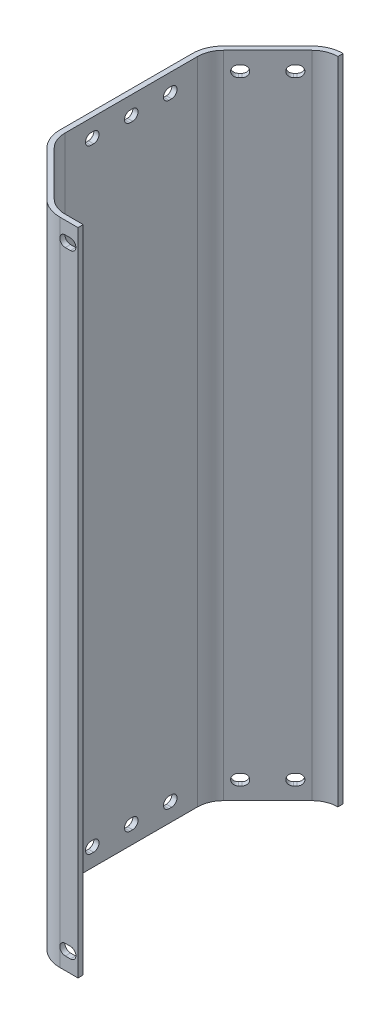
SolidWorks part; units mm, degrees
ref_plane "前视基准面" through (0, 0, 0) normal (0, 0, 1) x (1, 0, 0)
ref_plane "上视基准面" through (0, 0, 0) normal (0, 1, 0) x (1, 0, 0)
ref_plane "右视基准面" through (0, 0, 0) normal (1, 0, 0) x (0, 0, -1)
other "Configuration Table"
sketch "草图1" plane through (0, 0, 0) normal (0, 1, 0) x (1, 0, 0)
  line L0 (83.2331, 52.8648) -> (-81.774, 52.8648)
  line L1 (-88.8451, 49.9358) -> (-105.8415, 32.9394)
  line L2 (-108.7705, 25.8683) -> (-108.7705, -25.1388)
  line L3 (-105.8415, -32.2099) -> (-88.8451, -49.2063)
  line L4 (-81.774, -52.1352) -> (83.2331, -52.1352)
  line L5 (90.3042, -49.2063) -> (107.3006, -32.2099)
  line L6 (110.2295, -25.1388) -> (110.2295, 25.8683)
  line L7 (107.3006, 32.9394) -> (90.3042, 49.9358)
  arc A0 (-81.774, 52.8648) -> (-88.8451, 49.9358) centre (-81.774, 42.8648) ccw
  arc A1 (-105.8415, 32.9394) -> (-108.7705, 25.8683) centre (-98.7705, 25.8683) ccw
  arc A2 (-108.7705, -25.1388) -> (-105.8415, -32.2099) centre (-98.7705, -25.1388) ccw
  arc A3 (-88.8451, -49.2063) -> (-81.774, -52.1352) centre (-81.774, -42.1352) ccw
  arc A4 (83.2331, -52.1352) -> (90.3042, -49.2063) centre (83.2331, -42.1352) ccw
  arc A5 (107.3006, -32.2099) -> (110.2295, -25.1388) centre (100.2295, -25.1388) ccw
  arc A6 (110.2295, 25.8683) -> (107.3006, 32.9394) centre (100.2295, 25.8683) ccw
  arc A7 (90.3042, 49.9358) -> (83.2331, 52.8648) centre (83.2331, 42.8648) ccw
sketch "草图2" plane through (0, 0, 0) normal (0, 1, 0) x (1, 0, 0)
  line L0 (83.2331, 54.8648) -> (-81.774, 54.8648)
  line L1 (-90.2593, 51.35) -> (-107.2558, 34.3536)
  line L2 (-110.7705, 25.8683) -> (-110.7705, -25.1388)
  line L3 (-107.2558, -33.6241) -> (-90.2593, -50.6205)
  line L4 (-81.774, -54.1352) -> (83.2331, -54.1352)
  line L5 (91.7184, -50.6205) -> (108.7148, -33.6241)
  line L6 (112.2295, -25.1388) -> (112.2295, 25.8683)
  line L7 (108.7148, 34.3536) -> (91.7184, 51.35)
  line L8 (-81.774, -52.1352) -> (83.2331, -52.1352)
  line L9 (-105.8415, -32.2099) -> (-88.8451, -49.2063)
  line L10 (-108.7705, 25.8683) -> (-108.7705, -25.1388)
  line L11 (-88.8451, 49.9358) -> (-105.8415, 32.9394)
  line L12 (83.2331, 52.8648) -> (-81.774, 52.8648)
  line L13 (107.3006, 32.9394) -> (90.3042, 49.9358)
  line L14 (110.2295, -25.1388) -> (110.2295, 25.8683)
  line L15 (90.3042, -49.2063) -> (107.3006, -32.2099)
  line L16 (-81.774, -52.1352) -> (83.2331, -52.1352)
  line L17 (-105.8415, -32.2099) -> (-88.8451, -49.2063)
  line L18 (-108.7705, 25.8683) -> (-108.7705, -25.1388)
  line L19 (-88.8451, 49.9358) -> (-105.8415, 32.9394)
  line L20 (83.2331, 52.8648) -> (-81.774, 52.8648)
  line L21 (107.3006, 32.9394) -> (90.3042, 49.9358)
  line L22 (110.2295, -25.1388) -> (110.2295, 25.8683)
  line L23 (90.3042, -49.2063) -> (107.3006, -32.2099)
  line L24 (-74.774, 54.8648) -> (-74.774, 52.8648)
  line L25 (-74.774, -52.1352) -> (-74.774, -54.1352)
  line L26 (91.7184, 51.35) -> (90.3042, 49.9358)
  arc A0 (-81.774, 54.8648) -> (-90.2593, 51.35) centre (-81.774, 42.8648) ccw
  arc A1 (-107.2558, 34.3536) -> (-110.7705, 25.8683) centre (-98.7705, 25.8683) ccw
  arc A2 (-110.7705, -25.1388) -> (-107.2558, -33.6241) centre (-98.7705, -25.1388) ccw
  arc A3 (-90.2593, -50.6205) -> (-81.774, -54.1352) centre (-81.774, -42.1352) ccw
  arc A4 (83.2331, -54.1352) -> (91.7184, -50.6205) centre (83.2331, -42.1352) ccw
  arc A5 (108.7148, -33.6241) -> (112.2295, -25.1388) centre (100.2295, -25.1388) ccw
  arc A6 (112.2295, 25.8683) -> (108.7148, 34.3536) centre (100.2295, 25.8683) ccw
  arc A7 (91.7184, 51.35) -> (83.2331, 54.8648) centre (83.2331, 42.8648) ccw
  arc A8 (-88.8451, -49.2063) -> (-81.774, -52.1352) centre (-81.774, -42.1352) ccw
  arc A9 (-108.7705, -25.1388) -> (-105.8415, -32.2099) centre (-98.7705, -25.1388) ccw
  arc A10 (-105.8415, 32.9394) -> (-108.7705, 25.8683) centre (-98.7705, 25.8683) ccw
  arc A11 (-81.774, 52.8648) -> (-88.8451, 49.9358) centre (-81.774, 42.8648) ccw
  arc A12 (90.3042, 49.9358) -> (83.2331, 52.8648) centre (83.2331, 42.8648) ccw
  arc A13 (110.2295, 25.8683) -> (107.3006, 32.9394) centre (100.2295, 25.8683) ccw
  arc A14 (107.3006, -32.2099) -> (110.2295, -25.1388) centre (100.2295, -25.1388) ccw
  arc A15 (83.2331, -52.1352) -> (90.3042, -49.2063) centre (83.2331, -42.1352) ccw
  arc A16 (-88.8451, -49.2063) -> (-81.774, -52.1352) centre (-81.774, -42.1352) ccw
  arc A17 (-108.7705, -25.1388) -> (-105.8415, -32.2099) centre (-98.7705, -25.1388) ccw
  arc A18 (-105.8415, 32.9394) -> (-108.7705, 25.8683) centre (-98.7705, 25.8683) ccw
  arc A19 (-81.774, 52.8648) -> (-88.8451, 49.9358) centre (-81.774, 42.8648) ccw
  arc A20 (90.3042, 49.9358) -> (83.2331, 52.8648) centre (83.2331, 42.8648) ccw
  arc A21 (110.2295, 25.8683) -> (107.3006, 32.9394) centre (100.2295, 25.8683) ccw
  arc A22 (107.3006, -32.2099) -> (110.2295, -25.1388) centre (100.2295, -25.1388) ccw
  arc A23 (83.2331, -52.1352) -> (90.3042, -49.2063) centre (83.2331, -42.1352) ccw
  dimension "D3" = 7
  dimension "D4" = 7
  dimension "D1" = 0
  dimension "D2" = 2
extrude "凸台-拉伸1" add sketch "草图2" along normal blind 250
sketch "草图3" plane through (0, 0, -54.8648) normal (0, 0, -1) x (-1, 0, 0)
  line L0 (74.774, 125) -> (81.774, 125)
  line L1 (77.674, 243) -> (79.674, 243) construction
  line L2 (77.674, 245.1) -> (79.674, 245.1)
  line L3 (77.674, 240.9) -> (79.674, 240.9)
  line L4 (74.774, 0) -> (81.774, 0)
  line L5 (81.774, 0) -> (81.774, 250)
  line L6 (81.774, 250) -> (74.774, 250)
  line L7 (74.774, 250) -> (74.774, 0)
  line L8 (74.774, 0) -> (81.774, 0)
  line L9 (81.774, 0) -> (81.774, 250)
  line L10 (81.774, 250) -> (74.774, 250)
  line L11 (74.774, 250) -> (74.774, 0)
  line L12 (77.674, 7) -> (79.674, 7) construction
  line L13 (77.674, 4.9) -> (79.674, 4.9)
  line L14 (77.674, 9.1) -> (79.674, 9.1)
  arc A2 (77.674, 245.1) -> (77.674, 240.9) centre (77.674, 243) ccw
  arc A3 (79.674, 240.9) -> (79.674, 245.1) centre (79.674, 243) ccw
  arc A4 (77.674, 4.9) -> (77.674, 9.1) centre (77.674, 7) cw
  arc A5 (79.674, 9.1) -> (79.674, 4.9) centre (79.674, 7) cw
  point P12 (78.674, 243)
  point P20 (78.674, 7)
  dimension "D5" = 2.1
  dimension "D2" = 7
  dimension "D6" = 2
  dimension "D1" = 0
extrude "切除-拉伸2" cut sketch "草图3" against normal blind 250 contours A3 L2 A2 L3 | A5 L14 A4 L13
sketch "草图4" plane through (-70.8047, 0, -70.8047) normal (-0.7071, 0, -0.7071) x (-0.7071, 0, 0.7071)
  line L0 (39.5313, 250) -> (39.5313, 0) construction
  line L1 (27.513, 0) -> (51.5496, 0) construction
  line L2 (27.513, 7) -> (51.5496, 7) construction
  line L3 (31.5313, 7) -> (32.5313, 7) construction
  line L4 (27.513, 0) -> (51.5496, 0)
  line L5 (51.5496, 0) -> (51.5496, 250)
  line L6 (51.5496, 250) -> (27.513, 250)
  line L7 (27.513, 250) -> (27.513, 0)
  line L8 (27.513, 0) -> (51.5496, 0) construction
  line L9 (51.5496, 0) -> (51.5496, 250) construction
  line L10 (51.5496, 250) -> (27.513, 250) construction
  line L11 (27.513, 250) -> (27.513, 0) construction
  line L12 (31.5313, 9.1) -> (32.5313, 9.1)
  line L13 (31.5313, 4.9) -> (32.5313, 4.9)
  line L14 (47.5313, 7) -> (46.5313, 7) construction
  line L15 (47.5313, 9.1) -> (46.5313, 9.1)
  line L16 (47.5313, 4.9) -> (46.5313, 4.9)
  line L17 (27.513, 125) -> (51.5496, 125) construction
  line L18 (47.5313, 243) -> (46.5313, 243) construction
  line L19 (47.5313, 240.9) -> (46.5313, 240.9)
  line L20 (47.5313, 245.1) -> (46.5313, 245.1)
  line L21 (31.5313, 243) -> (32.5313, 243) construction
  line L22 (31.5313, 240.9) -> (32.5313, 240.9)
  line L23 (31.5313, 245.1) -> (32.5313, 245.1)
  arc A0 (31.5313, 9.1) -> (31.5313, 4.9) centre (31.5313, 7) ccw
  arc A1 (32.5313, 4.9) -> (32.5313, 9.1) centre (32.5313, 7) ccw
  arc A2 (47.5313, 9.1) -> (47.5313, 4.9) centre (47.5313, 7) cw
  arc A3 (46.5313, 4.9) -> (46.5313, 9.1) centre (46.5313, 7) cw
  arc A4 (47.5313, 240.9) -> (47.5313, 245.1) centre (47.5313, 243) ccw
  arc A5 (46.5313, 245.1) -> (46.5313, 240.9) centre (46.5313, 243) ccw
  arc A6 (31.5313, 240.9) -> (31.5313, 245.1) centre (31.5313, 243) cw
  arc A7 (32.5313, 245.1) -> (32.5313, 240.9) centre (32.5313, 243) cw
  point P12 (32.0313, 7)
  point P19 (47.0313, 7)
  point P28 (47.0313, 243)
  point P35 (32.0313, 243)
  dimension "D3" = 2.1
  dimension "D2" = 7
  dimension "D4" = 1
  dimension "D5" = 7.5
  dimension "D1" = 0
extrude "切除-拉伸4" cut sketch "草图4" against normal blind 250
sketch "草图5" plane through (-70.4399, 0, 70.4399) normal (-0.7071, 0, 0.7071) x (0.7071, 0, 0.7071)
  line L0 (-40.0472, 250) -> (-40.0472, 0) construction
  line L1 (-52.0654, 125) -> (-28.0289, 125) construction
  line L2 (-52.0654, 0) -> (-28.0289, 0) construction
  line L3 (-52.0654, 7) -> (-28.0289, 7) construction
  line L4 (-52.0654, 0) -> (-28.0289, 0)
  line L5 (-28.0289, 0) -> (-28.0289, 250)
  line L6 (-28.0289, 250) -> (-52.0654, 250)
  line L7 (-52.0654, 250) -> (-52.0654, 0)
  line L8 (-52.0654, 0) -> (-28.0289, 0) construction
  line L9 (-28.0289, 0) -> (-28.0289, 250) construction
  line L10 (-28.0289, 250) -> (-52.0654, 250) construction
  line L11 (-52.0654, 250) -> (-52.0654, 0) construction
  line L12 (-48.0472, 7) -> (-47.0472, 7) construction
  line L13 (-48.0472, 9.1) -> (-47.0472, 9.1)
  line L14 (-48.0472, 4.9) -> (-47.0472, 4.9)
  line L15 (-32.0472, 7) -> (-33.0472, 7) construction
  line L16 (-32.0472, 9.1) -> (-33.0472, 9.1)
  line L17 (-32.0472, 4.9) -> (-33.0472, 4.9)
  line L18 (-32.0472, 243) -> (-33.0472, 243) construction
  line L19 (-32.0472, 240.9) -> (-33.0472, 240.9)
  line L20 (-32.0472, 245.1) -> (-33.0472, 245.1)
  line L21 (-48.0472, 243) -> (-47.0472, 243) construction
  line L22 (-48.0472, 240.9) -> (-47.0472, 240.9)
  line L23 (-48.0472, 245.1) -> (-47.0472, 245.1)
  arc A0 (-48.0472, 9.1) -> (-48.0472, 4.9) centre (-48.0472, 7) ccw
  arc A1 (-47.0472, 4.9) -> (-47.0472, 9.1) centre (-47.0472, 7) ccw
  arc A2 (-32.0472, 9.1) -> (-32.0472, 4.9) centre (-32.0472, 7) cw
  arc A3 (-33.0472, 4.9) -> (-33.0472, 9.1) centre (-33.0472, 7) cw
  arc A4 (-32.0472, 240.9) -> (-32.0472, 245.1) centre (-32.0472, 243) ccw
  arc A5 (-33.0472, 245.1) -> (-33.0472, 240.9) centre (-33.0472, 243) ccw
  arc A6 (-48.0472, 240.9) -> (-48.0472, 245.1) centre (-48.0472, 243) cw
  arc A7 (-47.0472, 245.1) -> (-47.0472, 240.9) centre (-47.0472, 243) cw
  point P8 (-47.5472, 7)
  point P21 (-32.5472, 7)
  point P28 (-32.5472, 243)
  point P35 (-47.5472, 243)
  dimension "D3" = 2.1
  dimension "D2" = 7
  dimension "D4" = 1
  dimension "D5" = 7.5
  dimension "D1" = 0
extrude "切除-拉伸5" cut sketch "草图5" against normal blind 250
sketch "草图6" plane through (-110.7705, 0, 0) normal (-1, 0, 0) x (0, 0, 1)
  line L0 (-0.3648, 250) -> (-0.3648, 0) construction
  line L1 (-25.8683, 125) -> (25.1388, 125) construction
  line L2 (-25.8683, 7) -> (25.1388, 7) construction
  line L3 (-15.8648, 7) -> (-14.8648, 7) construction
  line L4 (-25.8683, 0) -> (25.1388, 0)
  line L5 (25.1388, 0) -> (25.1388, 250)
  line L6 (25.1388, 250) -> (-25.8683, 250)
  line L7 (-25.8683, 250) -> (-25.8683, 0)
  line L8 (-25.8683, 0) -> (25.1388, 0) construction
  line L9 (25.1388, 0) -> (25.1388, 250) construction
  line L10 (25.1388, 250) -> (-25.8683, 250) construction
  line L11 (-25.8683, 250) -> (-25.8683, 0) construction
  line L12 (-15.8648, 9.1) -> (-14.8648, 9.1)
  line L13 (-15.8648, 4.9) -> (-14.8648, 4.9)
  line L14 (-0.8648, 4.9) -> (0.1352, 4.9)
  line L15 (-0.8648, 9.1) -> (0.1352, 9.1)
  line L16 (-0.8648, 7) -> (0.1352, 7) construction
  line L17 (14.1352, 4.9) -> (15.1352, 4.9)
  line L18 (14.1352, 9.1) -> (15.1352, 9.1)
  line L19 (14.1352, 7) -> (15.1352, 7) construction
  line L20 (14.1352, 243) -> (15.1352, 243) construction
  line L21 (14.1352, 240.9) -> (15.1352, 240.9)
  line L22 (14.1352, 245.1) -> (15.1352, 245.1)
  line L23 (-0.8648, 243) -> (0.1352, 243) construction
  line L24 (-0.8648, 240.9) -> (0.1352, 240.9)
  line L25 (-0.8648, 245.1) -> (0.1352, 245.1)
  line L26 (-15.8648, 243) -> (-14.8648, 243) construction
  line L27 (-15.8648, 240.9) -> (-14.8648, 240.9)
  line L28 (-15.8648, 245.1) -> (-14.8648, 245.1)
  arc A0 (-15.8648, 9.1) -> (-15.8648, 4.9) centre (-15.8648, 7) ccw
  arc A1 (-14.8648, 4.9) -> (-14.8648, 9.1) centre (-14.8648, 7) ccw
  arc A2 (-0.8648, 9.1) -> (-0.8648, 4.9) centre (-0.8648, 7) ccw
  arc A3 (0.1352, 4.9) -> (0.1352, 9.1) centre (0.1352, 7) ccw
  arc A4 (14.1352, 9.1) -> (14.1352, 4.9) centre (14.1352, 7) ccw
  arc A5 (15.1352, 4.9) -> (15.1352, 9.1) centre (15.1352, 7) ccw
  arc A6 (14.1352, 240.9) -> (14.1352, 245.1) centre (14.1352, 243) cw
  arc A7 (15.1352, 245.1) -> (15.1352, 240.9) centre (15.1352, 243) cw
  arc A8 (-0.8648, 240.9) -> (-0.8648, 245.1) centre (-0.8648, 243) cw
  arc A9 (0.1352, 245.1) -> (0.1352, 240.9) centre (0.1352, 243) cw
  arc A10 (-15.8648, 240.9) -> (-15.8648, 245.1) centre (-15.8648, 243) cw
  arc A11 (-14.8648, 245.1) -> (-14.8648, 240.9) centre (-14.8648, 243) cw
  point P12 (-15.3648, 7)
  point P20 (-0.3648, 7)
  point P27 (14.6352, 7)
  point P34 (14.6352, 243)
  point P41 (-0.3648, 243)
  point P48 (-15.3648, 243)
  dimension "D4" = 2.1
  dimension "D2" = 7
  dimension "D3" = 1
  dimension "D6" = 15
  dimension "D1" = 0
  dimension "D5" = 3
extrude "切除-拉伸6" cut sketch "草图6" against normal blind 250
sketch "草图12" plane through (-74.774, 0, 0) normal (1, 0, 0) x (0, 0, -1)
  line L4 (52.8648, 0) -> (54.8648, 0)
  line L5 (54.8648, 0) -> (54.8648, 250)
  line L6 (54.8648, 250) -> (52.8648, 250)
  line L7 (52.8648, 250) -> (52.8648, 0)
  line L8 (52.8648, 0) -> (54.8648, 0)
  line L9 (54.8648, 0) -> (54.8648, 250)
  line L10 (54.8648, 250) -> (52.8648, 250)
  line L11 (52.8648, 250) -> (52.8648, 0)
  dimension "D1" = 0
extrude "切除-拉伸11" cut sketch "草图12" against normal blind 7
